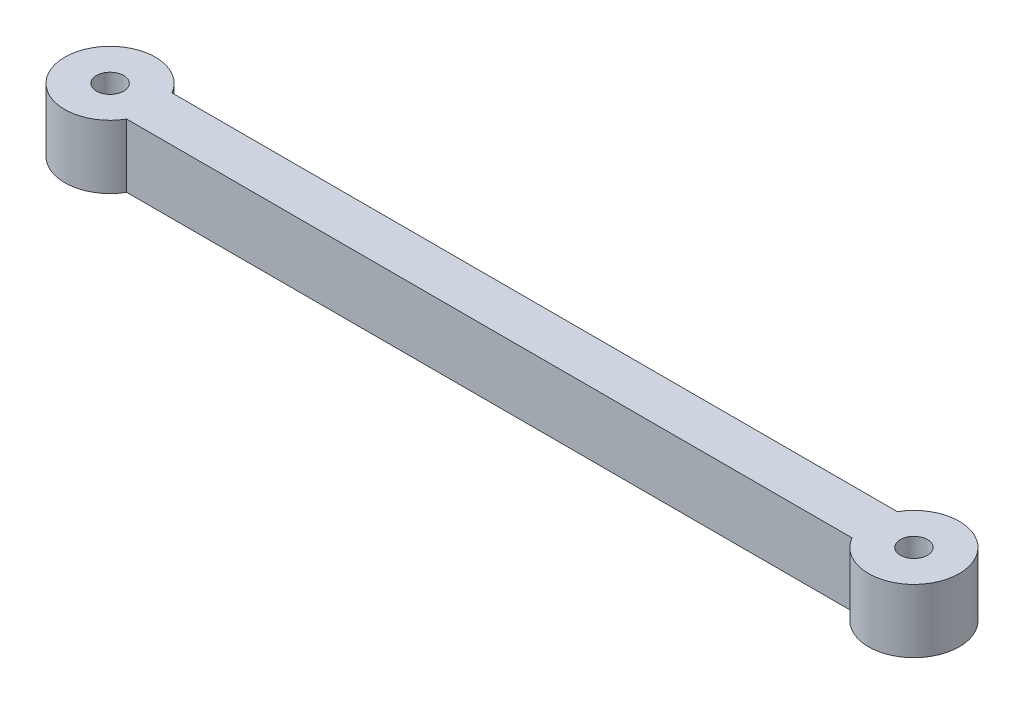
SolidWorks part; units mm, degrees
ref_plane "Front Plane" through (0, 0, 0) normal (0, 0, 1) x (1, 0, 0)
ref_plane "Top Plane" through (0, 0, 0) normal (0, 1, 0) x (1, 0, 0)
ref_plane "Right Plane" through (0, 0, 0) normal (1, 0, 0) x (0, 0, -1)
sketch "Sketch1" plane through (0, 0, 0) normal (0, 1, 0) x (1, 0, 0)
  line L0 (-40, 2.5) -> (40, 2.5)
  line L1 (-40, -2.5) -> (40, -2.5)
  line L2 (-55, 0) -> (55, 0) construction
  arc A1 (-40, 2.5) -> (-40, -2.5) centre (-44.3301, 0) ccw
  arc A2 (40, 2.5) -> (40, -2.5) centre (44.3301, 0) cw
  dimension "D2" = 40
  dimension "D3" = 5
  dimension "D7" = 5
  dimension "D1" = 5
  dimension "D4" = 80
  dimension "D5" = 80
  dimension "D6" = 2.5
extrude "Boss-Extrude1" add sketch "Sketch1" along normal blind 7
sketch "Sketch2" plane through (0, 7, 0) normal (0, 1, 0) x (1, 0, 0)
  circle A0 centre (-44.3301, 0) radius 1.5
  circle A1 centre (44.3301, 0) radius 1.5
  dimension "D1" = 3
  dimension "D2" = 3
extrude "Cut-Extrude1" cut sketch "Sketch2" against normal through all
